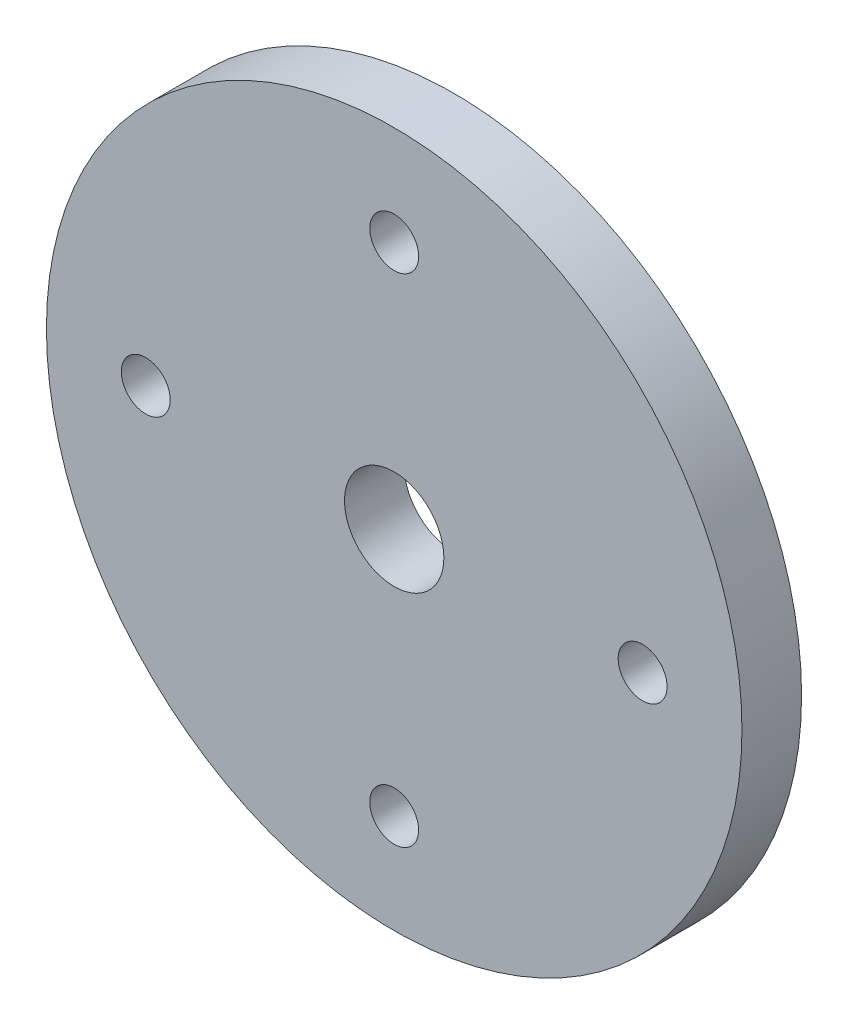
SolidWorks part; units mm, degrees
ref_plane "Front Plane" through (0, 0, 0) normal (0, 0, 1) x (1, 0, 0)
ref_plane "Top Plane" through (0, 0, 0) normal (0, 1, 0) x (1, 0, 0)
ref_plane "Right Plane" through (0, 0, 0) normal (1, 0, 0) x (0, 0, -1)
sketch "Sketch2" plane through (0, 0, 0) normal (0, 0, 1) x (1, 0, 0)
  circle A0 centre (0, 0) radius 17.5
  circle A1 centre (0, 0) radius 2.5
  circle A2 centre (0, 12.5) radius 1.23
  circle A3 centre (12.5, 0) radius 1.23
  circle A4 centre (0, -12.5) radius 1.23
  circle A5 centre (-12.5, 0) radius 1.23
  dimension "D1" = 35
  dimension "D2" = 5
  dimension "D3" = 2.46
  dimension "D4" = 12.5
  dimension "D5" = 4
extrude "Boss-Extrude1" add sketch "Sketch2" along normal blind 3
